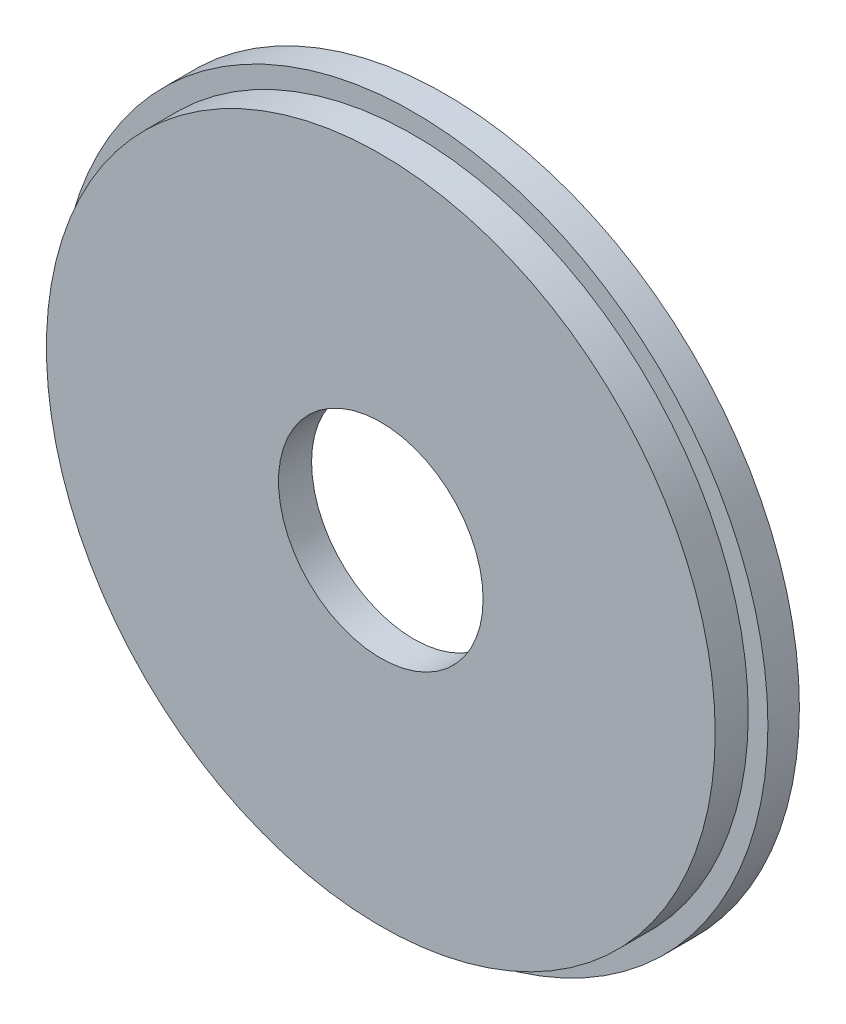
SolidWorks part; units mm, degrees
material "ABS"
ref_plane "Front Plane" through (0, 0, 0) normal (0, 0, 1) x (1, 0, 0)
ref_plane "Top Plane" through (0, 0, 0) normal (0, 1, 0) x (1, 0, 0)
ref_plane "Right Plane" through (0, 0, 0) normal (1, 0, 0) x (0, 0, -1)
sketch "Sketch1" plane through (0, 0, 0) normal (0, 0, 1) x (1, 0, 0)
  circle A0 centre (0, 0) radius 45
  dimension "D1" = 90
extrude "Boss-Extrude1" add sketch "Sketch1" along normal blind 4
sketch "Sketch2" plane through (0, 0, 4) normal (0, 0, 1) x (1, 0, 0)
  circle A1 centre (0, 0) radius 42.5
  dimension "D1" = 85
extrude "Boss-Extrude2" add sketch "Sketch2" along normal blind 4.2
sketch "Sketch4" plane through (0, 0, 8.2) normal (0, 0, 1) x (1, 0, 0)
  circle A0 centre (0, 0) radius 13
  dimension "D1" = 26
extrude "Cut-Extrude1" cut sketch "Sketch4" against normal through all
sketch "Sketch5" plane through (0, 0, 0) normal (0, 0, -1) x (-1, 0, 0)
  line L1 (-23, 30.5) -> (23, 30.5)
  line L2 (-23, 30.5) -> (-23, -30.5)
  line L3 (-23, -30.5) -> (23, -30.5)
  line L4 (23, 30.5) -> (23, -30.5)
  line L5 (-23, 30.5) -> (23, -30.5) construction
  line L6 (-23, -30.5) -> (23, 30.5) construction
  point P0 (0, 0)
  dimension "D1" = 61
  dimension "D2" = 46
extrude "Cut-Extrude2" cut sketch "Sketch5" against normal blind 4
